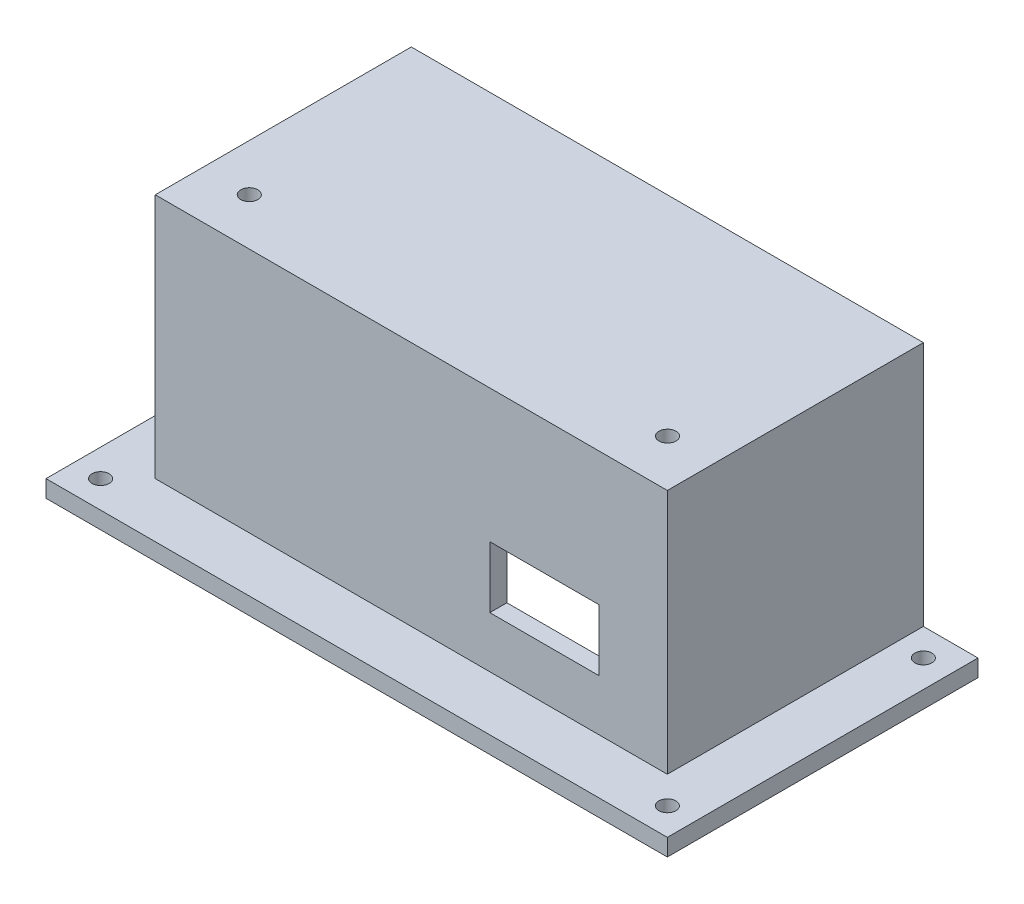
SolidWorks part; units mm, degrees
ref_plane "Front Plane" through (0, 0, 0) normal (0, 0, 1) x (1, 0, 0)
ref_plane "Top Plane" through (0, 0, 0) normal (0, 1, 0) x (1, 0, 0)
ref_plane "Right Plane" through (0, 0, 0) normal (1, 0, 0) x (0, 0, -1)
sketch "Sketch1" plane through (0, 0, 0) normal (0, 1, 0) x (1, 0, 0)
  line L1 (0, 0) -> (88.9, 0)
  line L2 (0, 0) -> (0, 44.45)
  line L3 (0, 44.45) -> (88.9, 44.45)
  line L4 (88.9, 0) -> (88.9, 44.45)
  dimension "D1" = 88.9
  dimension "D2" = 44.45
extrude "Boss-Extrude1" add sketch "Sketch1" along normal blind 3.175
sketch "Sketch2" plane through (0, 0, 0) normal (0, -1, 0) x (1, 0, 0)
  line L0 (0, 0) -> (88.9, 0) construction
  line L1 (-3.175, -44.45) -> (92.075, -44.45)
  line L2 (-3.175, -44.45) -> (-3.175, 3.175)
  line L3 (-3.175, 3.175) -> (92.075, 3.175)
  line L4 (92.075, -44.45) -> (92.075, 3.175)
  line L8 (0, 0) -> (0, -44.45)
  line L9 (0, -44.45) -> (88.9, -44.45)
  line L10 (88.9, -44.45) -> (88.9, 0)
  line L11 (88.9, 0) -> (0, 0)
  line L12 (0, 0) -> (0, -44.45)
  line L13 (0, -44.45) -> (88.9, -44.45)
  line L14 (88.9, -44.45) -> (88.9, 0)
  line L15 (88.9, 0) -> (0, 0)
  line M9 (0, 0) -> (0, -44.45)
  line M11 (88.9, -44.45) -> (88.9, 0)
  line M12 (88.9, 0) -> (0, 0)
  dimension "D2" = 3.175
  dimension "D3" = 3.175
  dimension "D4" = 3.175
  dimension "D1" = 0
extrude "Boss-Extrude2" add sketch "Sketch2" along normal blind 45.72 and the other way blind 3.175 contours L1 L4 L3 L2 M9 M12 M11
sketch "Sketch3" plane through (0, 0, 0) normal (0, -1, 0) x (1, 0, 0)
  line L0 (44.45, 0) -> (44.45, -38.336) construction
  line L1 (0, 0) -> (88.9, 0) construction
  circle A0 centre (83.3438, -5.588) radius 1.5875
  circle A1 centre (5.5562, -5.588) radius 1.5875
  point P8 (0, 0)
  dimension "D1" = 77.7875
  dimension "D3" = 3.175
  dimension "D2" = 5.588
extrude "Cut-Extrude1" cut sketch "Sketch3" against normal blind 45.72
sketch "Sketch4" plane through (0, -45.72, 0) normal (0, -1, 0) x (1, 0, 0)
  line L1 (-3.175, -44.45) -> (-13.335, -44.45)
  line L2 (-3.175, -44.45) -> (-3.175, 13.335)
  line L3 (-3.175, 13.335) -> (-13.335, 13.335)
  line L4 (-13.335, -44.45) -> (-13.335, 13.335)
  line L5 (-13.335, 13.335) -> (92.075, 13.335)
  line L6 (-13.335, 13.335) -> (-13.335, 3.175)
  line L7 (-13.335, 3.175) -> (92.075, 3.175)
  line L8 (92.075, 13.335) -> (92.075, 3.175)
  line L9 (92.075, -44.45) -> (102.235, -44.45)
  line L10 (92.075, -44.45) -> (92.075, 13.335)
  line L11 (92.075, 13.335) -> (102.235, 13.335)
  line L12 (102.235, -44.45) -> (102.235, 13.335)
  line M9 (92.075, -44.45) -> (92.075, 3.175)
  line M10 (92.075, 3.175) -> (-3.175, 3.175)
  line M11 (-3.175, 3.175) -> (-3.175, -44.45)
  dimension "D1" = 10.16
  dimension "D2" = 10.16
  dimension "D3" = 10.16
extrude "Boss-Extrude3" add sketch "Sketch4" against normal blind 3.175 contours L7 L4 L1 M11 | L4 L7 L2 L3 | L8 L5 L2 M10 | L9 L12 L11 L8 M9
sketch "Sketch5" plane through (0, -42.545, 0) normal (0, 1, 0) x (1, 0, 0)
  line L0 (-13.335, 44.45) -> (-13.335, -13.335) construction
  line L1 (-3.175, 44.45) -> (-13.335, 44.45) construction
  line L2 (102.235, -13.335) -> (-13.335, -13.335) construction
  line L3 (102.235, 44.45) -> (102.235, -13.335) construction
  circle A0 centre (-8.255, 39.37) radius 1.5875
  circle A1 centre (-8.255, -8.255) radius 1.5875
  circle A2 centre (97.155, -8.255) radius 1.5875
  circle A3 centre (97.155, 39.37) radius 1.5875
  point P16 (0, 0)
  point P17 (0, 0)
  point P18 (0, 0)
  point P19 (0, 0)
  dimension "D1" = 3.175
  dimension "D2" = 5.08
  dimension "D3" = 5.08
  dimension "D4" = 5.08
  dimension "D5" = 5.08
extrude "Cut-Extrude2" cut sketch "Sketch5" against normal blind 3.175
sketch "Sketch6" plane through (0, 0, 3.175) normal (0, 0, 1) x (1, 0, 0)
  line L0 (92.075, 3.175) -> (92.075, -42.545) construction
  line L1 (59.055, -21.59) -> (79.375, -21.59)
  line L2 (59.055, -21.59) -> (59.055, -33.02)
  line L3 (59.055, -33.02) -> (79.375, -33.02)
  line L4 (79.375, -21.59) -> (79.375, -33.02)
  line L5 (102.235, -45.72) -> (-13.335, -45.72) construction
  dimension "D1" = 12.7
  dimension "D2" = 20.32
  dimension "D3" = 11.43
  dimension "D4" = 12.7
extrude "Cut-Extrude3" cut sketch "Sketch6" against normal blind 3.175
sketch "Sketch7" plane through (0, 0, -44.45) normal (0, 0, -1) x (-1, 0, 0)
  line L0 (-88.9, 0) -> (-88.9, -45.72) construction
  line L1 (-88.9, -2.54) -> (0, -2.54)
  line L2 (-88.9, -2.54) -> (-88.9, 0)
  line L3 (-88.9, 0) -> (0, 0)
  line L4 (0, -2.54) -> (0, 0)
  line L5 (-88.9, -45.72) -> (0, -45.72) construction
  line L7 (0, -2.54) -> (-44.45, -2.54)
  line L8 (0, -2.54) -> (0, -15.24)
  line L9 (0, -15.24) -> (-44.45, -15.24)
  line L10 (-44.45, -2.54) -> (-44.45, -15.24)
  line M3 (-88.9, 0) -> (0, 0)
  line M4 (0, 0) -> (0, -45.72)
  line M14 (-88.9, -45.72) -> (-88.9, 0)
  dimension "D1" = 43.18
  dimension "D2" = 30.48
  dimension "D3" = 44.45
extrude "Boss-Extrude4" add sketch "Sketch7" against normal blind 3.175 contours L1 L10 L9 M4 | L1 M14 M4 M3
